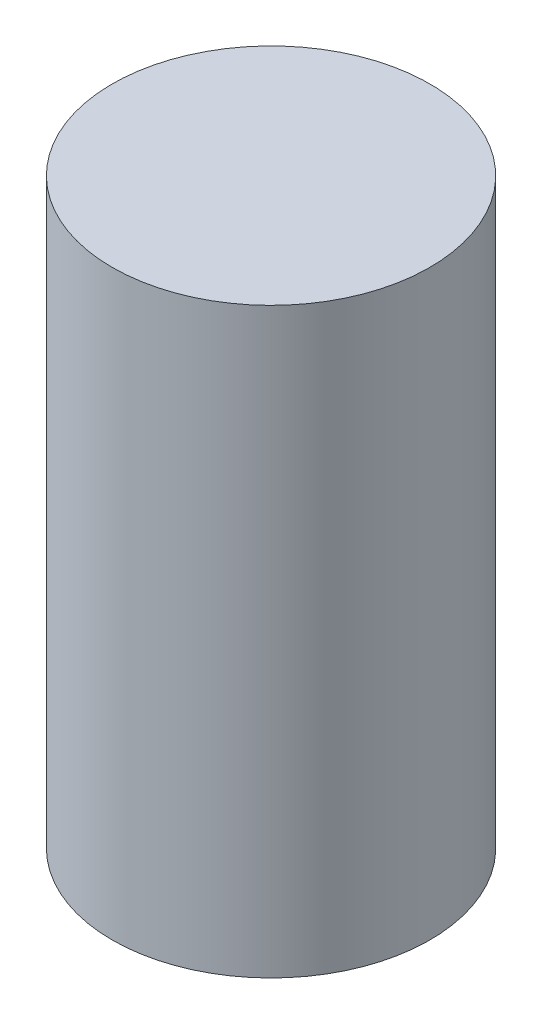
SolidWorks part; units mm, degrees
ref_plane "Plan de face" through (0, 0, 0) normal (0, 0, 1) x (1, 0, 0)
ref_plane "Plan de dessus" through (0, 0, 0) normal (0, 1, 0) x (1, 0, 0)
ref_plane "Plan de droite" through (0, 0, 0) normal (1, 0, 0) x (0, 0, -1)
sketch "Esquisse1" plane through (0, 0, 0) normal (0, 1, 0) x (1, 0, 0)
  circle A0 centre (-21.073, 7.2022) radius 12
extrude "Boss.-Extru.1" add sketch "Esquisse1" along normal blind 44
